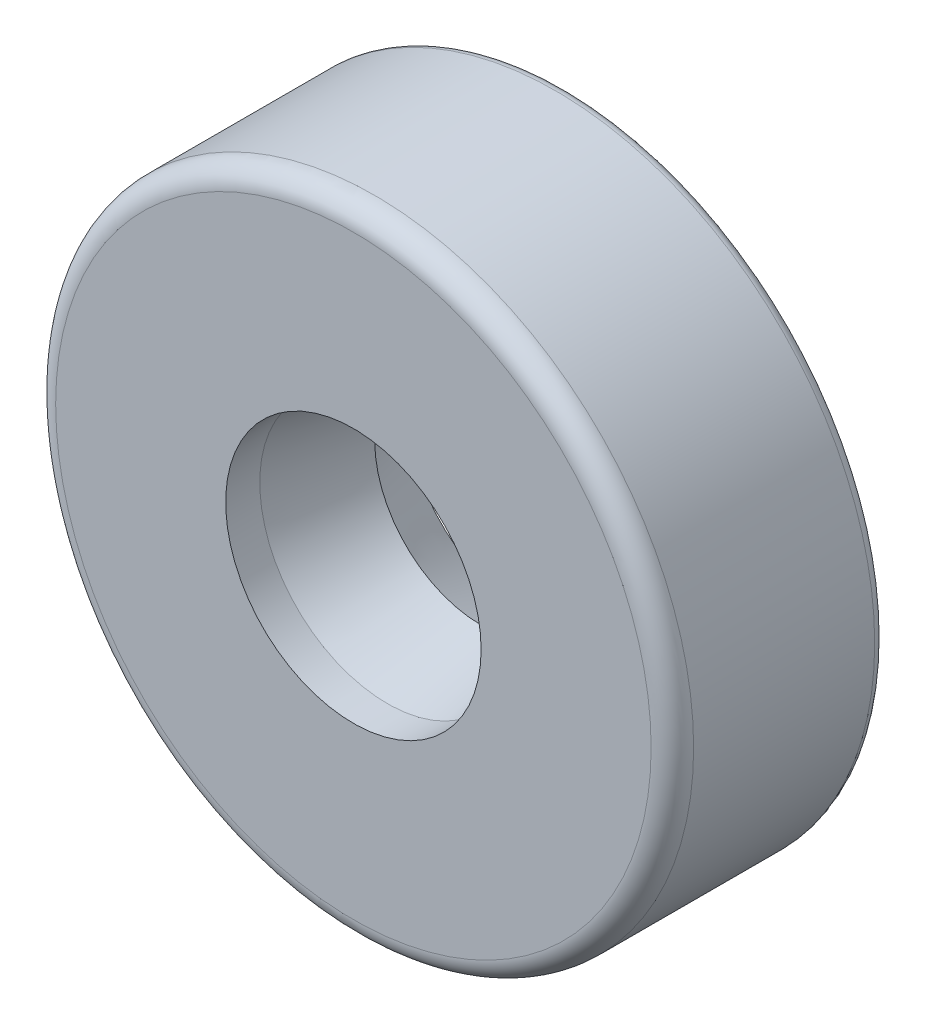
SolidWorks part; units mm, degrees
other "Markup1"
sketch "Sketch3" plane through (-9.5123, 9.5123, -3.175) normal (-0.1479, 0.305, -0.9408) x (-0.7997, 0.5228, 0.2953)
ref_plane "Front" through (0, 0, 0) normal (0, 0, 1) x (1, 0, 0)
ref_plane "Top" through (0, 0, 0) normal (0, 1, 0) x (1, 0, 0)
ref_plane "Right" through (0, 0, 0) normal (1, 0, 0) x (0, 0, -1)
sketch "Sketch1" plane through (0, 0, 0) normal (1, 0, 0) x (0, 0, -1)
  line L0 (-3.175, 8.8786) -> (-3.175, 3.8087)
  line L1 (-3.175, 3.8087) -> (-2.159, 3.8087)
  line L2 (-2.159, 3.8087) -> (0.635, 3.175)
  line L3 (0.635, 3.175) -> (2.159, 3.8087)
  line L4 (2.159, 3.8087) -> (2.159, 4.4425)
  line L5 (2.159, 4.4425) -> (1.1499, 4.4425)
  line L6 (0.1201, 4.4425) -> (-2.159, 4.4425)
  line L7 (-2.159, 4.4425) -> (-2.159, 8.3637)
  line L8 (-1.6441, 8.8786) -> (2.6997, 8.8786)
  line L9 (2.9953, 8.7994) -> (3.1325, 8.7201)
  line L10 (3.175, 8.8786) -> (3.175, 9.1954)
  line L11 (2.8581, 9.5123) -> (-2.5413, 9.5123)
  line L12 (3.175, 0) -> (-3.175, 0) construction
  line L13 (-3.175, 6.3437) -> (-1.905, 6.3437) construction
  line L14 (-1.905, 6.3437) -> (-0.635, 6.3437) construction
  line L15 (-0.635, 6.3437) -> (0.635, 6.3437) construction
  line L16 (0.635, 6.3437) -> (1.905, 6.3437) construction
  line L17 (3.175, 8.8786) -> (3.175, 6.3437) construction
  line L18 (0.635, 6.3437) -> (0.635, 4.4425) construction
  line L19 (1.905, 6.3437) -> (3.175, 6.3437) construction
  line L20 (0.1584, 9.5123) -> (0.1584, 8.8786) construction
  line L21 (0.1584, 8.8786) -> (0.1584, 8.2448) construction
  line L22 (0.1584, 8.2448) -> (0.1584, 7.6111) construction
  line L23 (0.1584, 7.6111) -> (0.1584, 6.9774) construction
  line L24 (0.1584, 6.9774) -> (0.1584, 6.3437) construction
  line L25 (0.1584, 6.3437) -> (0.1584, 5.7099) construction
  line L26 (0.1584, 5.7099) -> (0.1584, 5.0762) construction
  line L27 (0.1584, 5.0762) -> (0.1584, 4.4425) construction
  line L28 (-2.159, 3.8087) -> (0.1584, 3.8087) construction
  line L29 (0.1584, 4.4425) -> (0.1584, 3.8087) construction
  line L30 (0.1584, 3.8087) -> (0.1584, 3.175) construction
  line L31 (0.1584, 3.175) -> (0.635, 3.175) construction
  line L32 (0.635, 4.4425) -> (0.635, 3.175) construction
  line L33 (-3.175, 8.8786) -> (-2.5413, 8.8786) construction
  line L34 (3.175, 9.1954) -> (2.5413, 9.1954) construction
  line L35 (2.8581, 8.8786) -> (2.9953, 8.7994) construction
  line L36 (2.8581, 8.8786) -> (2.8581, 9.037) construction
  line L37 (-3.175, 5.7099) -> (-2.667, 5.7099) construction
  line L38 (-2.667, 5.7099) -> (-2.159, 5.7099) construction
  line L39 (-2.159, 5.7099) -> (-1.651, 5.7099) construction
  line L40 (-1.651, 5.7099) -> (-1.143, 5.7099) construction
  line L41 (-1.143, 5.7099) -> (-0.635, 5.7099) construction
  line L42 (-0.635, 5.7099) -> (-0.127, 5.7099) construction
  line L43 (-0.127, 5.7099) -> (0.381, 5.7099) construction
  line L44 (0.381, 5.7099) -> (0.889, 5.7099) construction
  line L45 (0.889, 5.7099) -> (1.397, 5.7099) construction
  line L46 (1.397, 5.7099) -> (1.905, 5.7099) construction
  line L47 (1.905, 5.7099) -> (2.413, 5.7099) construction
  line L48 (3.175, 6.3437) -> (3.175, 5.7099) construction
  line L49 (3.429, 5.7099) -> (2.921, 5.7099) construction
  line L50 (2.921, 5.7099) -> (2.413, 5.7099) construction
  line L51 (2.159, 4.4425) -> (2.159, 5.7099) construction
  line L52 (0, 6.3437) -> (0, 0) construction
  arc A0 (1.1499, 4.4425) -> (0.1201, 4.4425) centre (0.635, 4.4425) ccw construction
  arc A1 (-2.159, 8.3637) -> (-1.6441, 8.8786) centre (-1.6441, 8.3637) cw
  arc A2 (2.6997, 8.8786) -> (2.9953, 8.7994) centre (2.8581, 8.8786) cw
  arc A3 (3.1325, 8.7201) -> (3.175, 8.8786) centre (2.8581, 8.8786) ccw
  arc A4 (3.175, 9.1954) -> (2.8581, 9.5123) centre (2.8581, 9.1954) ccw
  arc A5 (-2.5413, 9.5123) -> (-3.175, 8.8786) centre (-2.5413, 8.8786) ccw
  arc A6 (0.1201, 4.4425) -> (1.1499, 4.4425) centre (0.635, 4.4425) ccw
  dimension "D3" = 0.5149
  dimension "D5" = 0.1584
  dimension "D6" = 0.3169
  dimension "D4" = 60
revolve "Revolve1" add sketch "Sketch1" angle 360 about L12
sketch "Sketch2" plane through (0, 0, 0) normal (1, 0, 0) x (0, 0, -1)
  line L0 (-3.175, 0) -> (3.175, 0) construction
  circle A0 centre (0.635, 4.4425) radius 0.5149
revolve "Revolve2" add sketch "Sketch2" angle 360 about L0
equation "\"D5@Sketch1\"=\"D6@Sketch1\"/2"
equation "\"D3@Sketch1\"=\"D6@Sketch1\"*1.625"
